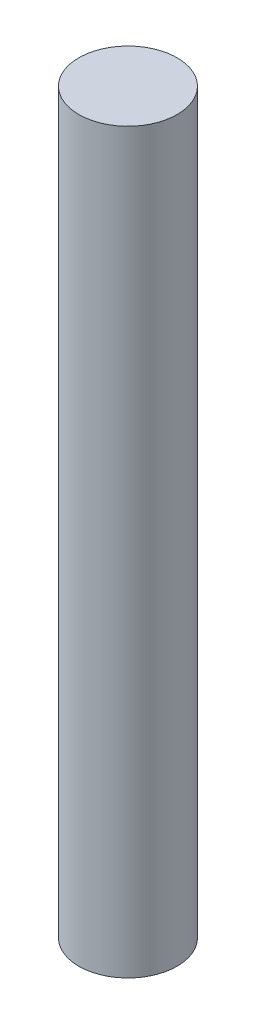
SolidWorks part; units mm, degrees
material "PE High Density"
ref_plane "Front Plane" through (0, 0, 0) normal (0, 0, 1) x (1, 0, 0)
ref_plane "Top Plane" through (0, 0, 0) normal (0, 1, 0) x (1, 0, 0)
ref_plane "Right Plane" through (0, 0, 0) normal (1, 0, 0) x (0, 0, -1)
sketch "Sketch1" plane through (0, 0, 0) normal (0, 1, 0) x (1, 0, 0)
  circle A0 centre (0, 0) radius 10
  dimension "D1" = 20
extrude "Boss-Extrude1" add sketch "Sketch1" along normal blind 150
scale "Scale1" scale about centroid uniform scaling yes scale factor 0.75
